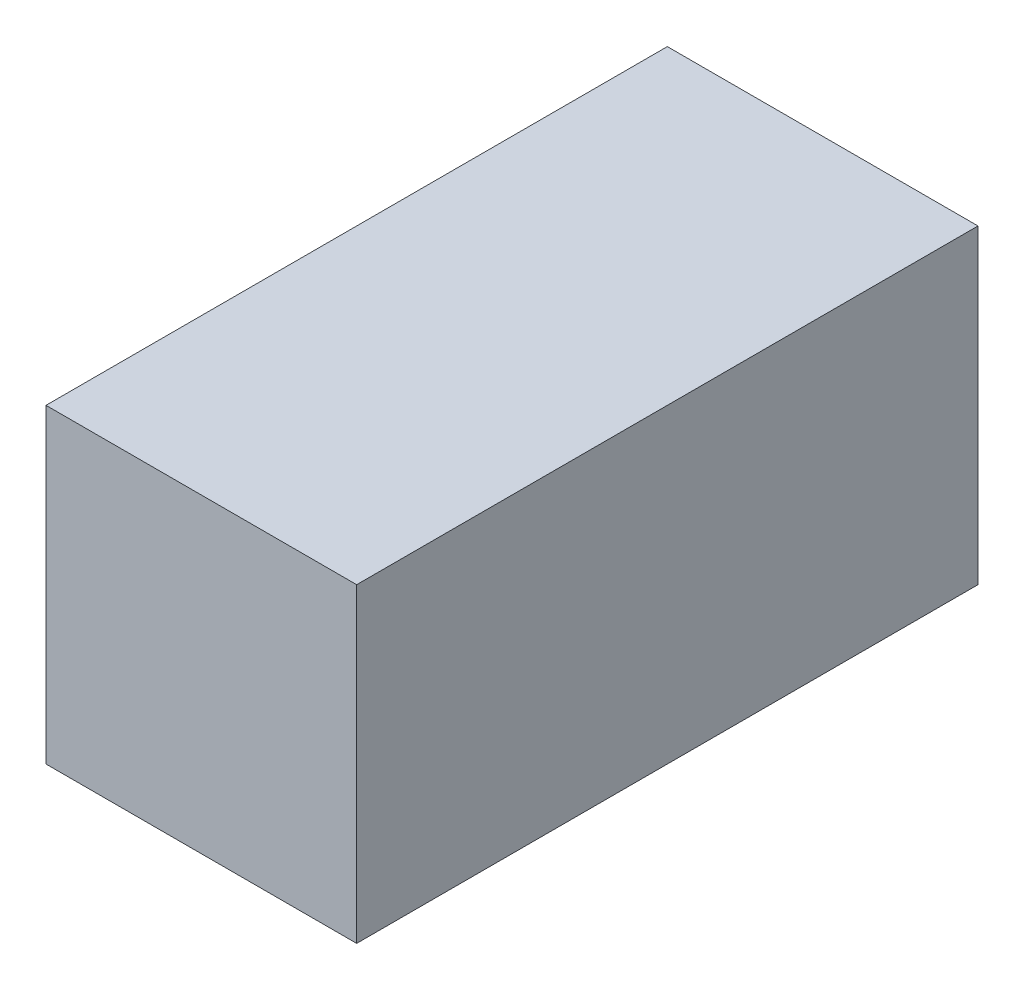
SolidWorks part; units mm, degrees
ref_plane "Front Plane" through (0, 0, 0) normal (0, 0, 1) x (1, 0, 0)
ref_plane "Top Plane" through (0, 0, 0) normal (0, 1, 0) x (1, 0, 0)
ref_plane "Right Plane" through (0, 0, 0) normal (1, 0, 0) x (0, 0, -1)
sketch "Sketch1" plane through (0, 0, 0) normal (1, 0, 0) x (0, 0, -1)
  line L1 (0, 0) -> (20, 0)
  line L2 (0, 0) -> (0, 10)
  line L3 (0, 10) -> (20, 10)
  line L4 (20, 0) -> (20, 10)
  dimension "D1" = 10
  dimension "D2" = 20
extrude "Boss-Extrude1" add sketch "Sketch1" along normal blind 10
